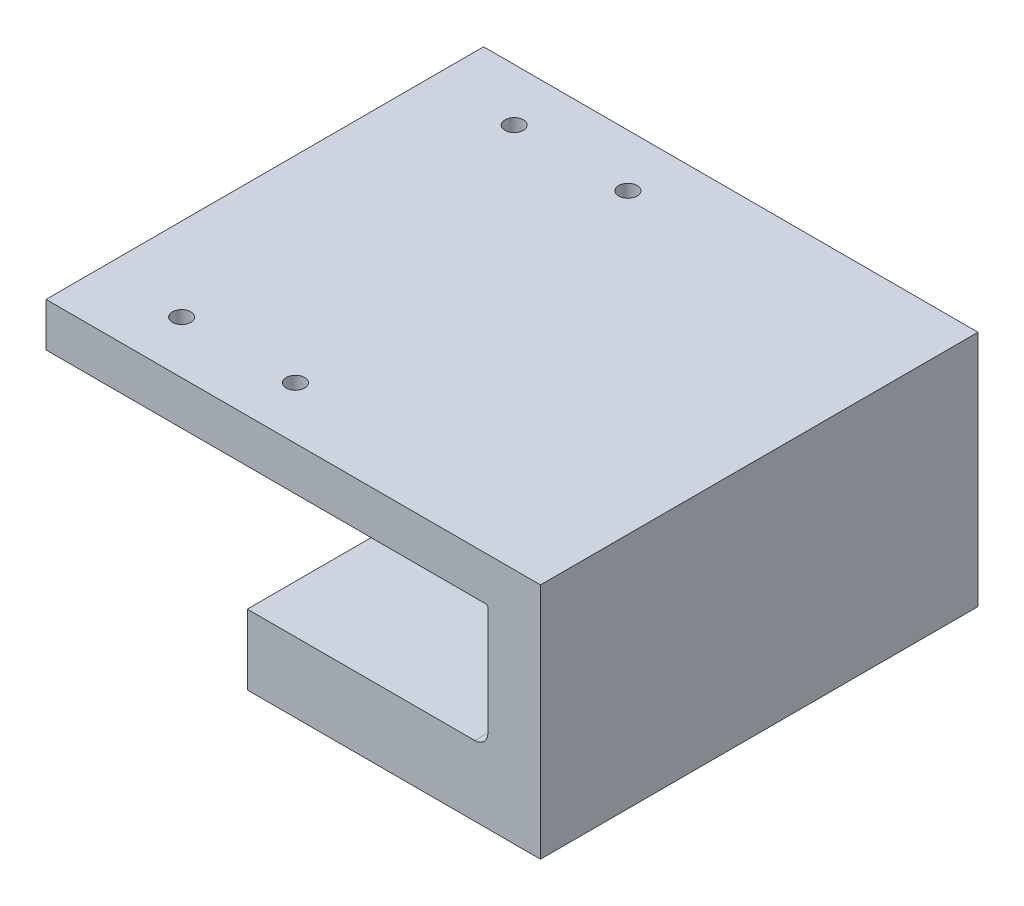
SolidWorks part; units mm, degrees
ref_plane "Front Plane" through (0, 0, 0) normal (0, 0, 1) x (1, 0, 0)
ref_plane "Top Plane" through (0, 0, 0) normal (0, 1, 0) x (1, 0, 0)
ref_plane "Right Plane" through (0, 0, 0) normal (1, 0, 0) x (0, 0, -1)
sketch "Sketch1" plane through (0, 0, 0) normal (0, 0, 1) x (1, 0, 0)
  line L0 (0, 0) -> (0, 10)
  line L1 (0, 10) -> (113, 10)
  line L2 (113, 10) -> (113, -44.3)
  line L3 (113, -44.3) -> (46, -44.3)
  line L4 (46, -44.3) -> (46, -28.3)
  line L5 (46, -28.3) -> (101, -28.3)
  line L6 (101, -28.3) -> (101, 0)
  line L7 (101, 0) -> (0, 0)
  dimension "D1" = 10
  dimension "D2" = 113
  dimension "D3" = 16
  dimension "D4" = 55
  dimension "D5" = 12
  dimension "D6" = 28.3
extrude "Boss-Extrude1" add sketch "Sketch1" along normal blind 100
sketch "Sketch3" plane through (0, 10, 0) normal (0, 1, 0) x (1, 0, 0)
  line L0 (0, -100) -> (0, 0) construction
  line L1 (113, 0) -> (0, 0) construction
  circle A0 centre (19, -12) radius 2.1
  circle A1 centre (19, -88) radius 2.1
  circle A2 centre (45, -12) radius 2.1
  circle A3 centre (45, -88) radius 2.1
  point P10 (0, 0)
  point P13 (68.0487, -18.8287)
  point P14 (0, 0)
  point P15 (0, 0)
  point P16 (0, 0)
  point P17 (0, 0)
  point P18 (0, 0)
  dimension "D4" = 4.2
  dimension "D5" = 4.2
  dimension "D6" = 4.2
  dimension "D7" = 4.2
  dimension "D1" = 45
  dimension "D2" = 76
  dimension "D3" = 12
  dimension "D9" = 19
sketch "Sketch4" plane through (0, -44.3, 0) normal (0, -1, 0) x (1, 0, 0)
  line L0 (113, 100) -> (113, 0) construction
  line L1 (46, 100) -> (113, 100) construction
  circle A0 centre (66, 50) radius 4.3
  dimension "D1" = 8.6
  dimension "D2" = 47
  dimension "D3" = 50
extrude "Cut-Extrude1" cut sketch "Sketch4" against normal blind 16
sketch "Sketch5" plane through (46, 0, 0) normal (-1, 0, 0) x (0, 0, 1)
  line L0 (0, -28.3) -> (0, -44.3) construction
  line L1 (43.35, -32.15) -> (56.65, -32.15)
  line L2 (43.35, -32.15) -> (43.35, -40.45)
  line L3 (43.35, -40.45) -> (56.65, -40.45)
  line L4 (56.65, -32.15) -> (56.65, -40.45)
  line L5 (100, -44.3) -> (0, -44.3) construction
  dimension "D1" = 13.3
  dimension "D2" = 8.3
  dimension "D3" = 43.35
  dimension "D4" = 3.85
extrude "Cut-Extrude2" cut sketch "Sketch5" against normal blind 27
extrude "Cut-Extrude3" cut sketch "Sketch3" against normal blind 8
sketch "Sketch6" plane through (0, -44.3, 0) normal (0, -1, 0) x (1, 0, 0)
  line L0 (113, 100) -> (113, 0) construction
  line L1 (66, 56.08) -> (62.96, 53.04)
  line L2 (62.96, 53.04) -> (66, 50)
  line L3 (66, 50) -> (69.04, 53.04)
  line L4 (69.04, 53.04) -> (66, 56.08)
  line L5 (46, 100) -> (113, 100) construction
  circle A0 centre (66, 53.04) radius 3.04 construction
  point P10 (0, 0)
  dimension "D1" = 6.08
  dimension "D2" = 47
  dimension "D3" = 46.96
extrude "Cut-Extrude4" cut sketch "Sketch6" against normal blind 16
fillet "Fillet1" radius 3 1 edges at (101, -28.3, 50)
fillet "Fillet2" radius 0.5 1 edges at (101, 0, 50)
